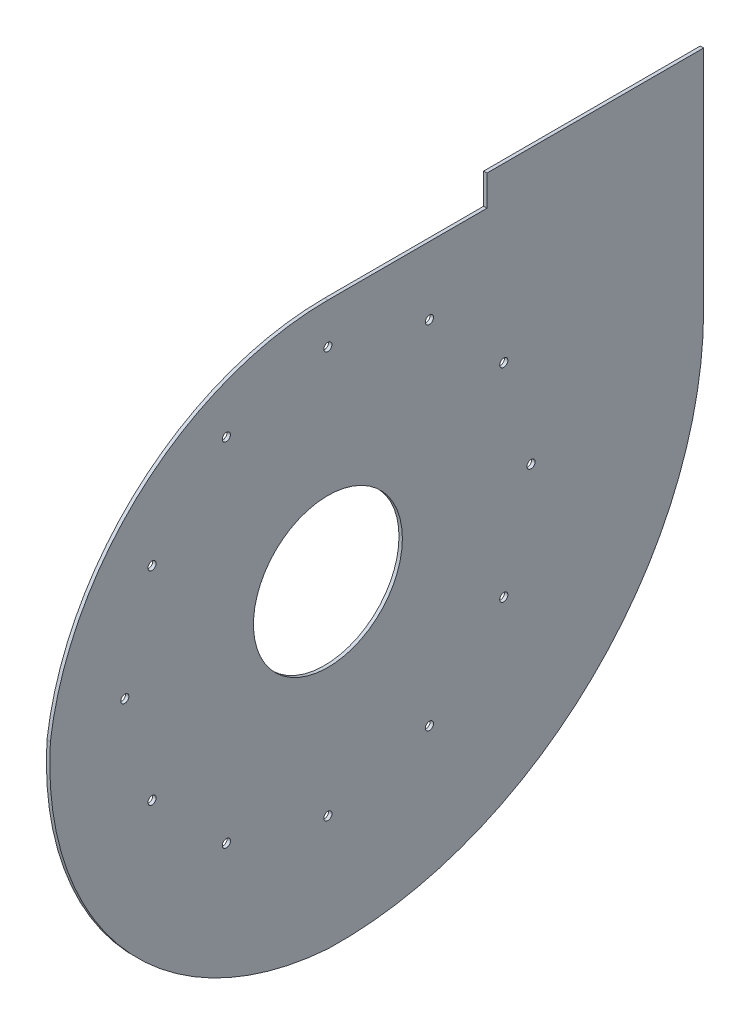
SolidWorks part; units mm, degrees
material "ASTM A36 Steel"
ref_plane "Front Plane" through (0, 0, 0) normal (0, 0, 1) x (1, 0, 0)
ref_plane "Top Plane" through (0, 0, 0) normal (0, 1, 0) x (1, 0, 0)
ref_plane "Right Plane" through (0, 0, 0) normal (1, 0, 0) x (0, 0, -1)
sketch "Sketch1" plane through (0, 0, 0) normal (1, 0, 0) x (0, 0, -1)
  line L0 (-126.9857, 168.7705) -> (193.0143, 168.7705)
  line L1 (-126.9857, 168.7705) -> (-126.9857, 123.7705)
  line L3 (-126.9857, 123.7705) -> (-361.9857, 123.7705)
  line L6 (193.0143, 168.7705) -> (193.0143, -166.6252)
  circle A0 centre (-361.9857, -236.2295) radius 110
  arc A1 (-361.9857, 123.7705) -> (-771.9857, -236.2295) centre (-361.5606, -290.1858) ccw
  arc A2 (-771.9857, -236.2295) -> (-361.9857, -706.2295) centre (-329.7472, -264.2768) ccw
  arc A3 (193.0143, -166.6252) -> (-361.9857, -706.2295) centre (-346.8035, -166.6252) cw
  dimension "D4" = 220
  dimension "D1" = 320
  dimension "D2" = 45
  dimension "D3" = 360
  dimension "D5" = 410
  dimension "D6" = 470
extrude "Boss-Extrude1" add sketch "Sketch1" along normal blind 5
sketch "Sketch2" plane through (0, 0, 0) normal (-1, 0, 0) x (0, 0, 1)
  circle A1 centre (661.9857, -236.2295) radius 6
  circle A2 centre (361.9857, -236.2295) radius 110 construction
  dimension "D1" = 300
  dimension "D2" = 12
extrude "Cut-Extrude1" cut sketch "Sketch2" against normal blind 10
pattern_circular "CirPattern1" count 12 every 30 about axis through (0, -236.2295, 361.9857) along (1, 0, 0) of "Cut-Extrude1"
